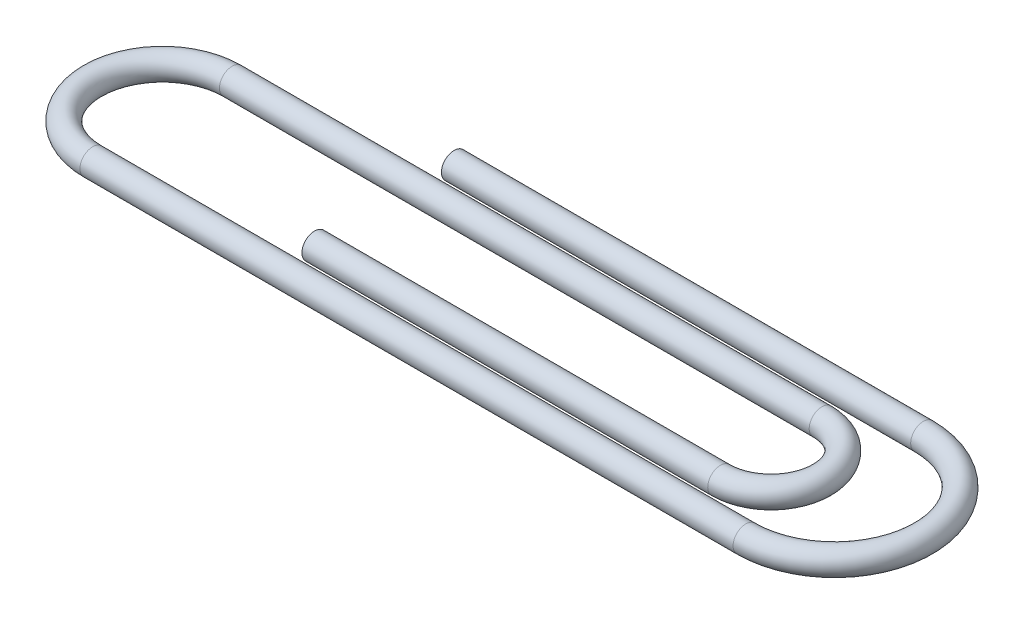
SolidWorks part; units mm, degrees
ref_plane "Front Plane" through (0, 0, 0) normal (0, 0, 1) x (1, 0, 0)
ref_plane "Top Plane" through (0, 0, 0) normal (0, 1, 0) x (1, 0, 0)
ref_plane "Right Plane" through (0, 0, 0) normal (1, 0, 0) x (0, 0, -1)
sketch "Sketch1" plane through (0, 0, 0) normal (1, 0, 0) x (0, 0, -1)
  circle A0 centre (0, 0) radius 0.5
  dimension "D1" = 1
sketch "Sketch3" plane through (0, 0, 0) normal (0, 1, 0) x (1, 0, 0)
  line L0 (0, 0) -> (18.5, 0)
  line L1 (0, -0.5) -> (0, 0.5) construction
  line L2 (18.5, -7) -> (-7.25, -7)
  line L3 (-7.25, -1.5) -> (16, -1.5)
  line L4 (16, -5.5) -> (0, -5.5)
  arc A0 (18.5, -7) -> (18.5, 0) centre (18.5, -3.5) ccw
  arc A1 (-7.25, -1.5) -> (-7.25, -7) centre (-7.25, -4.25) ccw
  arc A2 (16, -5.5) -> (16, -1.5) centre (16, -3.5) ccw
  point P5 (-10, -4.25)
  point P9 (22, -3.5)
  point P13 (18, -3.5)
  point P16 (14.2226, -2.7459)
  dimension "D2" = 2.75
  dimension "D3" = 3.5
  dimension "D4" = 2
  dimension "D1" = 18.5
  dimension "D5" = 32
  dimension "D6" = 10
  dimension "D7" = 4
sweep "Sweep1" add profiles "Sketch1" path "Sketch3"
